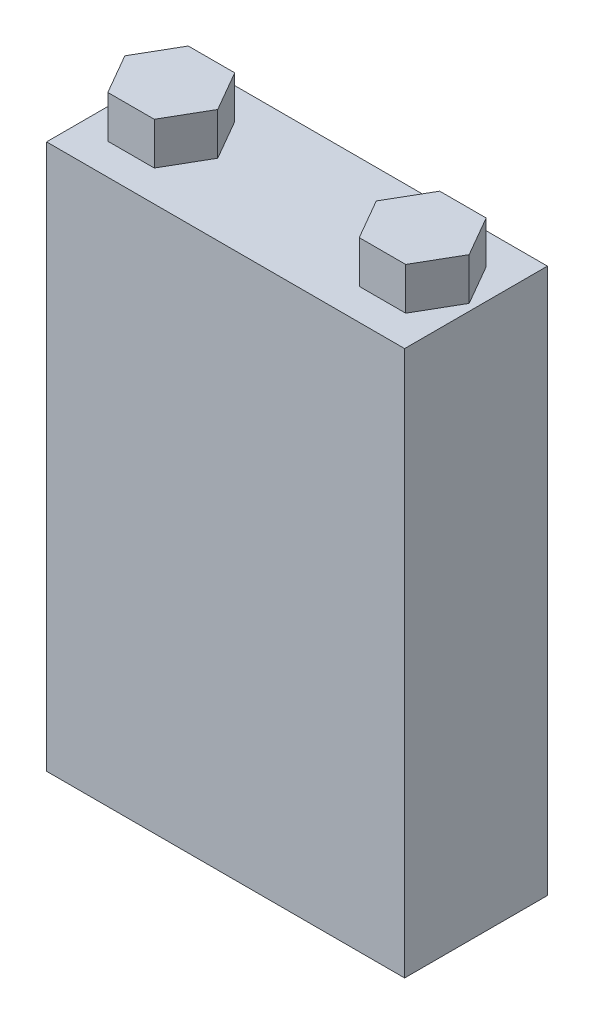
SolidWorks part; units mm, degrees
material "battery"
ref_plane "Front" through (0, 0, 0) normal (0, 0, 1) x (1, 0, 0)
ref_plane "Top" through (0, 0, 0) normal (0, 1, 0) x (1, 0, 0)
ref_plane "Right" through (0, 0, 0) normal (1, 0, 0) x (0, 0, -1)
sketch "Sketch1" plane through (0, 0, 0) normal (0, 1, 0) x (1, 0, 0)
  line L1 (-89, 35.5) -> (89, 35.5)
  line L2 (-89, 35.5) -> (-89, -35.5)
  line L3 (-89, -35.5) -> (89, -35.5)
  line L4 (89, 35.5) -> (89, -35.5)
  line L5 (-89, 35.5) -> (89, -35.5) construction
  line L6 (-89, -35.5) -> (89, 35.5) construction
  point P0 (0, 0)
  dimension "D1" = 178
  dimension "D2" = 71
extrude "Boss-Extrude1" add sketch "Sketch1" along normal blind 271
sketch "Sketch2" plane through (0, 271, 0) normal (0, 1, 0) x (1, 0, 0)
  line L0 (-62.5, 0) -> (0, 0) construction
  line L1 (-39.406, 0) -> (-50.953, 20)
  line L2 (-50.953, 20) -> (-74.047, 20)
  line L3 (-74.047, 20) -> (-85.594, 0)
  line L4 (-85.594, 0) -> (-74.047, -20)
  line L5 (-74.047, -20) -> (-50.953, -20)
  line L6 (-50.953, -20) -> (-39.406, 0)
  line L7 (85.594, 0) -> (74.047, 20)
  line L8 (74.047, 20) -> (50.953, 20)
  line L9 (50.953, 20) -> (39.406, 0)
  line L10 (39.406, 0) -> (50.953, -20)
  line L11 (50.953, -20) -> (74.047, -20)
  line L12 (74.047, -20) -> (85.594, 0)
  line L13 (0, 0) -> (62.5, 0) construction
  circle A0 centre (-62.5, 0) radius 20 construction
  circle A1 centre (62.5, 0) radius 20 construction
  dimension "D1" = 40
  dimension "D2" = 125
extrude "Boss-Extrude2" add sketch "Sketch2" along normal blind 21
